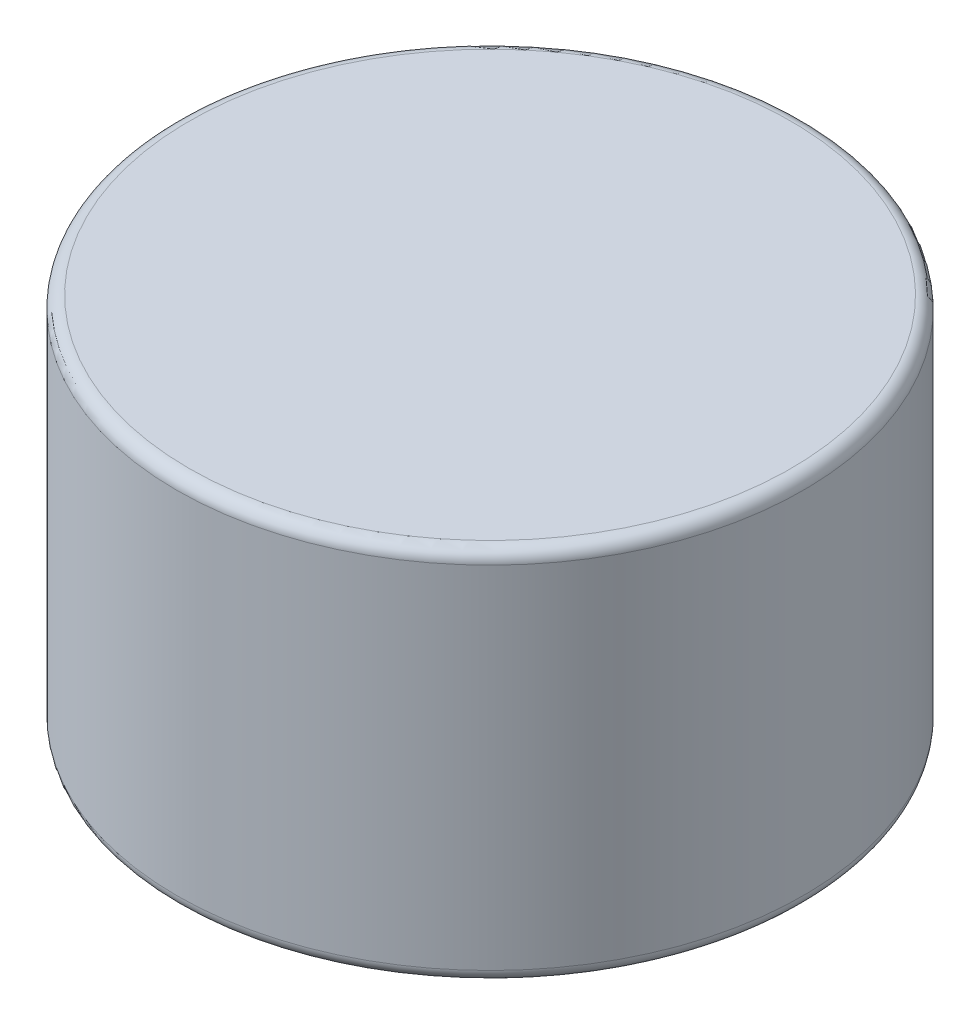
SolidWorks part; units mm, degrees
ref_plane "Front Plane" through (0, 0, 0) normal (0, 0, 1) x (1, 0, 0)
ref_plane "Top Plane" through (0, 0, 0) normal (0, 1, 0) x (1, 0, 0)
ref_plane "Right Plane" through (0, 0, 0) normal (1, 0, 0) x (0, 0, -1)
sketch "Sketch1" plane through (0, 0, 0) normal (0, 1, 0) x (1, 0, 0)
  circle A0 centre (0, 0) radius 2.5
  dimension "D1" = 5
extrude "Boss-Extrude1" add sketch "Sketch1" along normal blind 3
fillet "Fillet1" radius 0.1 2 edges at (0, 0, 2.5) (0, 3, 2.5)
